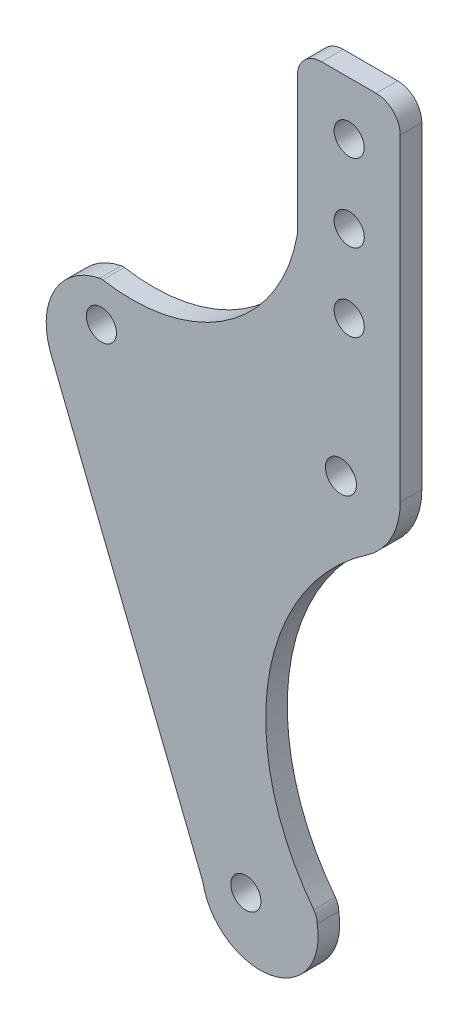
SolidWorks part; units mm, degrees
ref_plane "Front Plane" through (0, 0, 0) normal (0, 0, 1) x (1, 0, 0)
ref_plane "Top Plane" through (0, 0, 0) normal (0, 1, 0) x (1, 0, 0)
ref_plane "Right Plane" through (0, 0, 0) normal (1, 0, 0) x (0, 0, -1)
sketch "Sketch1" plane through (0, 0, 0) normal (0, 0, 1) x (1, 0, 0)
  line L0 (0, 0) -> (0, 30.156) construction
  line L1 (0, 0) -> (32.4691, 0) construction
  line L3 (-26.683, 26.3577) -> (-26.683, 6.3518)
  line L4 (-15.0841, 29.9137) -> (-23.127, 29.9137)
  line L5 (-63.1034, -26.9607) -> (-40.5959, -83.4559)
  line L7 (-11.5281, -20.4623) -> (-11.5281, 26.3577)
  line L8 (-40.5959, -83.4559) -> (-24.2809, -78.8021) construction
  circle A0 centre (-55.5441, -19.825) radius 2.2225
  circle A1 centre (-19.05, 22.085) radius 2.2225
  circle A2 centre (-19.05, -0.775) radius 2.2225
  arc A6 (-15.0841, 29.9137) -> (-11.5281, 26.3577) centre (-15.0841, 26.3577) cw
  arc A7 (-23.127, 29.9137) -> (-26.683, 26.3577) centre (-23.127, 26.3577) ccw
  arc A9 (-16.357, -29.5947) -> (-24.2809, -78.8021) centre (2.9569, -57.9465) ccw
  arc A11 (-16.357, -29.5947) -> (-11.5281, -20.4623) centre (-22.5782, -20.4623) ccw
  circle A14 centre (-34.2687, -81.6511) radius 2.2225
  arc A17 (-23.7579, -80.3848) -> (-24.2809, -78.8021) centre (-26.2976, -80.3463) ccw
  arc A21 (-40.5959, -83.4559) -> (-23.7579, -80.3848) centre (-32.1769, -81.9204) ccw
  arc A23 (-63.1034, -26.9607) -> (-55.7802, -14.0251) centre (-53.8578, -23.6541) cw
  circle A24 centre (-19.05, 10.655) radius 2.2225
  arc A25 (-55.3282, -14.0195) -> (-26.7251, 5.891) centre (-51.0844, 10.3846) ccw
  arc A26 (-55.3282, -14.0195) -> (-55.7802, -14.0251) centre (-55.5392, -15.2326) ccw
  arc A27 (-26.683, 6.3518) -> (-26.7251, 5.891) centre (-29.223, 6.3518) cw
  point P14 (-19.1056, 29.9137)
  point P24 (-15.2948, 26.5068)
  point P35 (-55.5441, -13.981)
  point P41 (-55.5441, -13.981)
  dimension "D1" = 2.2225
  dimension "D2" = 2.54
  dimension "D3" = 3.556
  dimension "D4" = 34.3053
  dimension "D5" = 11.0501
  dimension "D6" = 8.5579
  dimension "D7" = 9.8191
  dimension "D11" = 11.5281
  dimension "D12" = 15.2948
  dimension "D13" = 19.05
  dimension "D10" = 2.9569
  dimension "D14" = 19.1056
  dimension "D15" = 24.2809
  dimension "D18" = 53.8578
  dimension "D19" = 55.3282
  dimension "D21" = 26.5068
  dimension "D22" = 29.9137
  dimension "D23" = 32.1769
  dimension "D24" = 34.2687
  dimension "D8" = 24.7703
  dimension "D9" = 1.2313
  dimension "D16" = 26.7251
  dimension "D17" = 23.7579
  dimension "D20" = 5.891
  dimension "D25" = 40.5959
  dimension "D26" = 10.655
  dimension "D27" = 22.085
  dimension "D28" = 20.4623
  dimension "D30" = 0.775
  dimension "D32" = 63.1034
  dimension "D36" = 19.825
extrude "Boss-Extrude1" add sketch "Sketch1" along normal blind 3.175
sketch "Sketch2" plane through (0, 0, 3.175) normal (0, 0, 1) x (1, 0, 0)
  line L0 (-11.5281, -20.4623) -> (-11.5281, 26.3577) construction
  line L1 (-15.0841, 29.9137) -> (-23.127, 29.9137) construction
  circle A0 centre (-20.2675, -21.5169) radius 2.286
  dimension "D1" = 4.572
  dimension "D2" = 8.7394
  dimension "D3" = 51.4306
extrude "Cut-Extrude1" cut sketch "Sketch2" against normal through all
